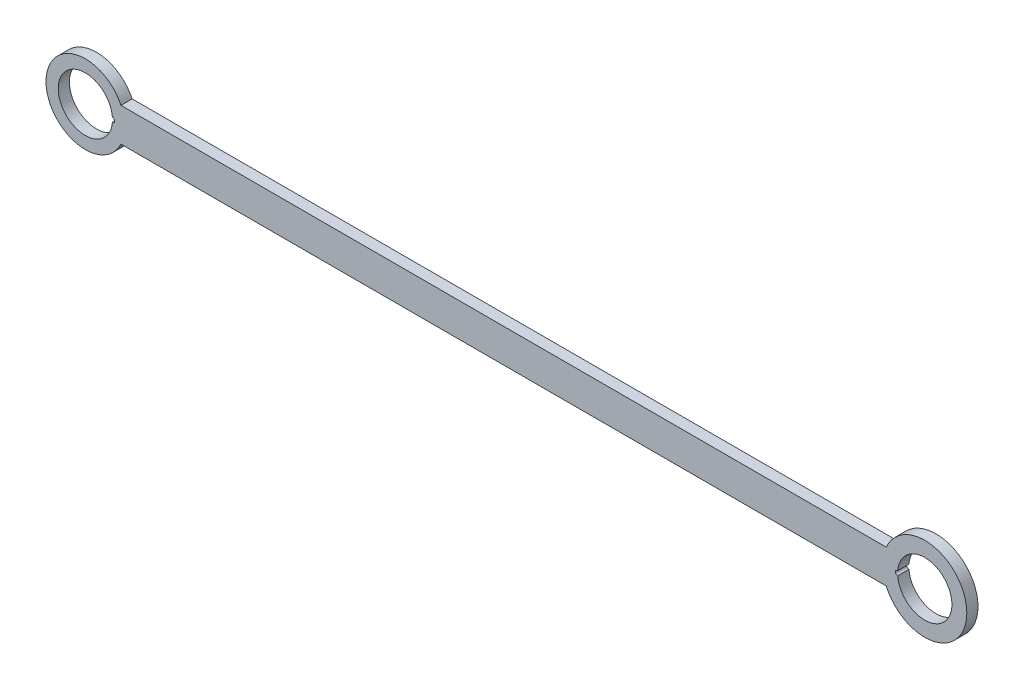
SolidWorks part; units mm, degrees
ref_plane "前视基准面" through (0, 0, 0) normal (0, 0, 1) x (1, 0, 0)
ref_plane "上视基准面" through (0, 0, 0) normal (0, 1, 0) x (1, 0, 0)
ref_plane "右视基准面" through (0, 0, 0) normal (1, 0, 0) x (0, 0, -1)
sketch "草图1" plane through (0, 0, 0) normal (0, 0, 1) x (1, 0, 0)
  line L0 (0, 0) -> (300, 0) construction
  line L1 (12.7187, 6) -> (286.2245, 6)
  line L2 (35.8014, 6) -> (35.8014, 0) construction
  line L3 (12.7187, -6) -> (286.2245, -6)
  line L4 (35.8014, 0) -> (35.8014, -6) construction
  circle A0 centre (0, 0) radius 9.7
  circle A1 centre (300, 0) radius 9.7
  circle A2 centre (0, 0) radius 14.0629 construction
  circle A3 centre (300, 0) radius 15.0255 construction
  arc A4 (12.7187, -6) -> (12.7187, 6) centre (0, 0) cw
  arc A5 (286.2245, -6) -> (286.2245, 6) centre (300, 0) ccw
  dimension "D1" = 19.4
  dimension "D3" = 6
  dimension "D2" = 300
extrude "凸台-拉伸1" add sketch "草图1" along normal blind 4 contours L3 A5 L1 A4
sketch "草图3" plane through (0, 0, 4) normal (0, 0, 1) x (1, 0, 0)
  circle A0 centre (9.7, 0) radius 0.8
  circle A1 centre (0, 0) radius 9.7 construction
  circle A2 centre (290.3, 0) radius 0.8
  circle A3 centre (300, 0) radius 9.7 construction
extrude "切除-拉伸1" cut sketch "草图3" against normal blind 10
